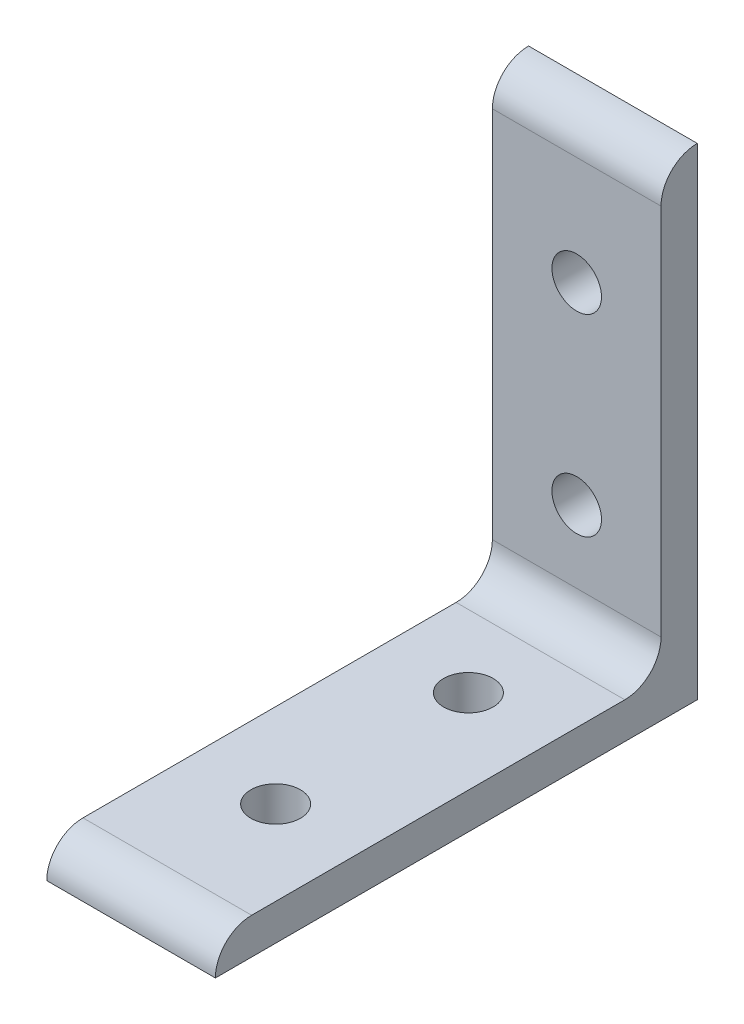
SolidWorks part; units mm, degrees
material "6061 Alloy"
ref_plane "Front Plane" through (0, 0, 0) normal (0, 0, 1) x (1, 0, 0)
ref_plane "Top Plane" through (0, 0, 0) normal (0, 1, 0) x (1, 0, 0)
ref_plane "Right Plane" through (0, 0, 0) normal (1, 0, 0) x (0, 0, -1)
ref_plane "Plane1" through (22.225, 0, 0) normal (1, 0, 0) x (0, 0, -1)
sketch "Sketch1" plane through (22.225, 0, 0) normal (1, 0, 0) x (0, 0, -1)
  line L0 (-39.5292, -29.6061) -> (23.9708, -29.6061)
  line L1 (23.9708, -29.6061) -> (23.9708, 33.8939)
  line L2 (19.1956, 29.1187) -> (19.1956, -24.8309)
  line L3 (19.1956, -24.8309) -> (-34.754, -24.8309)
  arc A0 (-34.754, -24.8309) -> (-39.5292, -29.6061) centre (-34.754, -29.6061) ccw
  arc A1 (23.9708, 33.8939) -> (19.1956, 29.1187) centre (23.9708, 29.1187) ccw
extrude "Boss-Extrude1" add sketch "Sketch1" against normal blind 22.225
hole_wizard "Hole1" positions "Sketch3" profile "Sketch2" legacy
sketch "Sketch3" plane through (0, 0, -23.9708) normal (0, 0, -1) x (-1, 0, 0)
  point P0 (-11.1125, -10.5561)
sketch "Sketch2" plane through (11.1125, -10.5561, -23.9708) normal (1, 0, 0) x (0, 1, 0)
  line L0 (0, 0) -> (0, 63.5)
  line L1 (0, 63.5) -> (3.2639, 63.5)
  line L2 (3.2639, 63.5) -> (3.2639, 0)
  line L3 (3.2639, 0) -> (0, 0)
  line L4 (0, 110) -> (0, -10) construction
  dimension "Diameter" = 6.5278
  dimension "Depth" = 63.5
hole_wizard "Hole2" positions "Sketch5" profile "Sketch4" legacy
sketch "Sketch5" plane through (0, 0, -23.9708) normal (0, 0, -1) x (-1, 0, 0)
  point P0 (-11.1125, 14.8439)
sketch "Sketch4" plane through (11.1125, 14.8439, -23.9708) normal (1, 0, 0) x (0, 1, 0)
  line L0 (0, 0) -> (0, 63.5)
  line L1 (0, 63.5) -> (3.2639, 63.5)
  line L2 (3.2639, 63.5) -> (3.2639, 0)
  line L3 (3.2639, 0) -> (0, 0)
  line L4 (0, 110) -> (0, -10) construction
  dimension "Diameter" = 6.5278
  dimension "Depth" = 63.5
hole_wizard "Hole3" positions "Sketch7" profile "Sketch6" legacy
sketch "Sketch7" plane through (0, -29.6061, 0) normal (0, -1, 0) x (1, 0, 0)
  point P0 (11.1125, -4.9208)
sketch "Sketch6" plane through (11.1125, -29.6061, -4.9208) normal (1, 0, 0) x (0, 0, -1)
  line L0 (0, 0) -> (0, 63.5)
  line L1 (0, 63.5) -> (3.2639, 63.5)
  line L2 (3.2639, 63.5) -> (3.2639, 0)
  line L3 (3.2639, 0) -> (0, 0)
  line L4 (0, 110) -> (0, -10) construction
  dimension "Diameter" = 6.5278
  dimension "Depth" = 63.5
hole_wizard "Hole4" positions "Sketch9" profile "Sketch8" legacy
sketch "Sketch9" plane through (0, -29.6061, 0) normal (0, -1, 0) x (1, 0, 0)
  point P0 (11.1125, 20.4792)
sketch "Sketch8" plane through (11.1125, -29.6061, 20.4792) normal (1, 0, 0) x (0, 0, -1)
  line L0 (0, 0) -> (0, 63.5)
  line L1 (0, 63.5) -> (3.2639, 63.5)
  line L2 (3.2639, 63.5) -> (3.2639, 0)
  line L3 (3.2639, 0) -> (0, 0)
  line L4 (0, 110) -> (0, -10) construction
  dimension "Diameter" = 6.5278
  dimension "Depth" = 63.5
fillet "Fillet1" radius 4.7752 1 edges at (11.1125, -24.8309, -19.1956)
